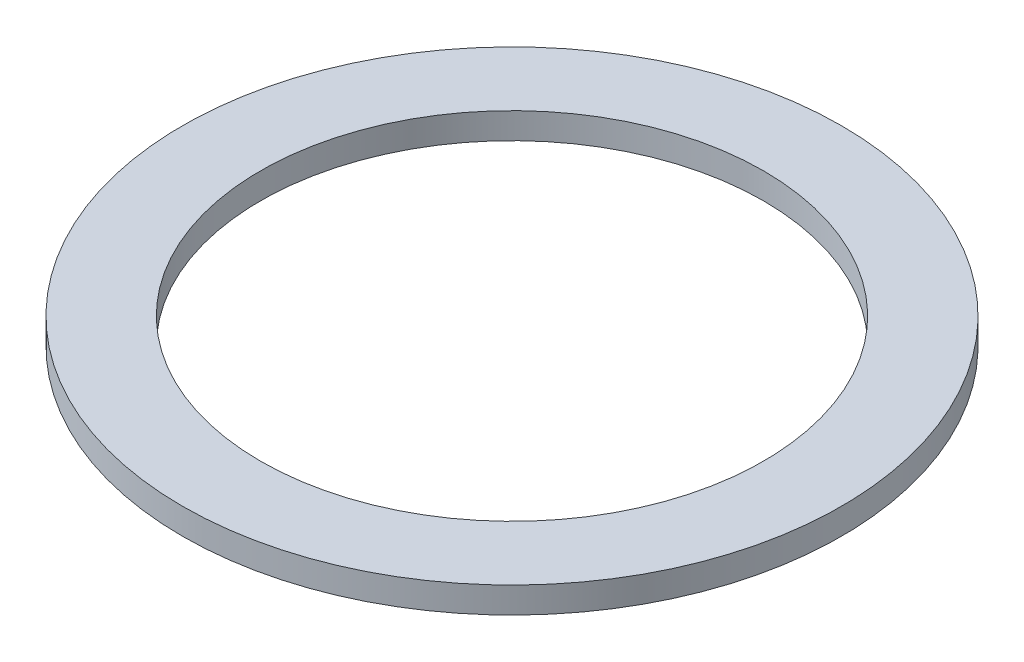
SolidWorks part; units mm, degrees
ref_plane "Front Plane" through (0, 0, 0) normal (0, 0, 1) x (1, 0, 0)
ref_plane "Top Plane" through (0, 0, 0) normal (0, 1, 0) x (1, 0, 0)
ref_plane "Right Plane" through (0, 0, 0) normal (1, 0, 0) x (0, 0, -1)
sketch "Sketch1" plane through (0, 0, 0) normal (0, 1, 0) x (1, 0, 0)
  circle A0 centre (0, 0) radius 29
  circle A1 centre (0, 0) radius 38
  dimension "D1" = 58
  dimension "D2" = 76
extrude "Boss-Extrude1" add sketch "Sketch1" along normal blind 3
